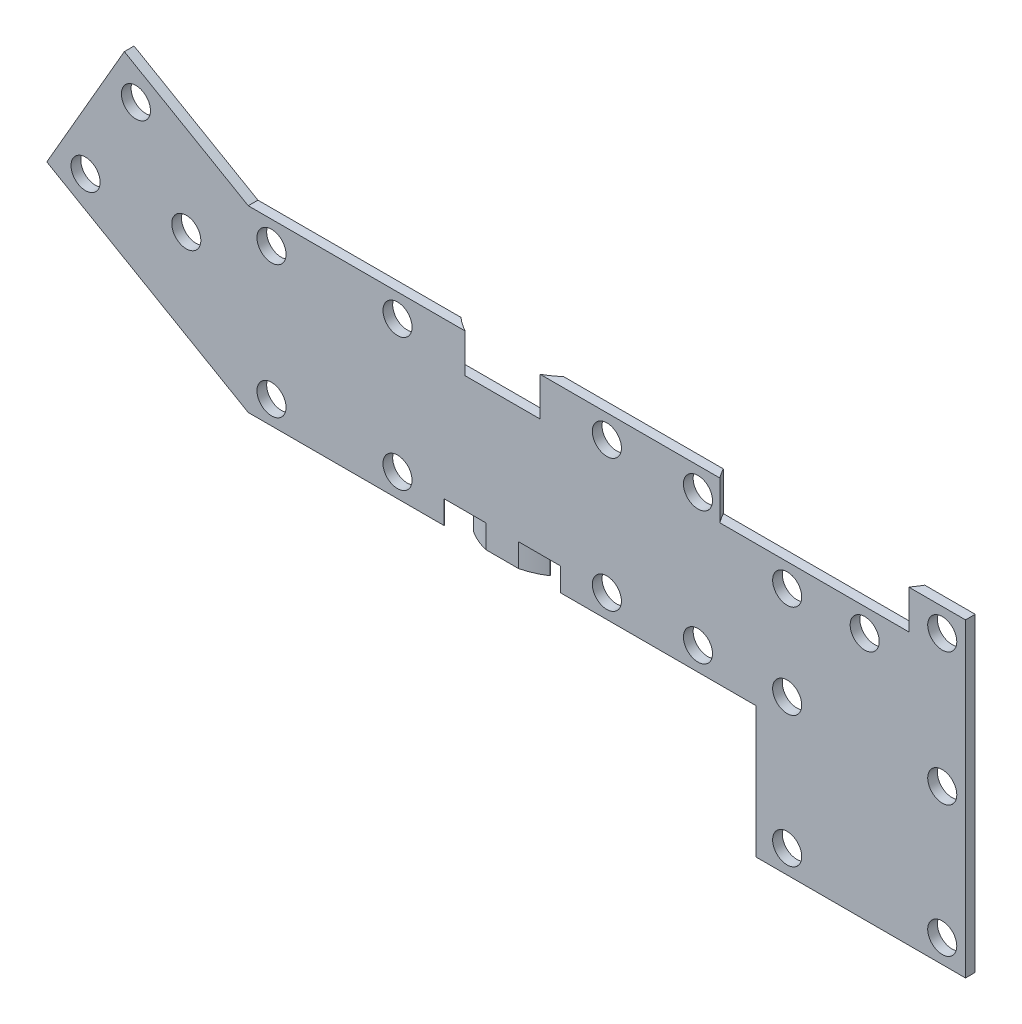
SolidWorks part; units mm, degrees
material "1023 Carbon Steel Sheet (SS)"
ref_plane "Front Plane" through (0, 0, 0) normal (0, 0, 1) x (1, 0, 0)
ref_plane "Top Plane" through (0, 0, 0) normal (0, 1, 0) x (1, 0, 0)
ref_plane "Right Plane" through (0, 0, 0) normal (1, 0, 0) x (0, 0, -1)
sketch "Sketch1" plane through (0, 0, 0) normal (0, 0, 1) x (1, 0, 0)
  line L0 (0, 0) -> (-40.5911, 23.4353)
  line L1 (-40.5911, 23.4353) -> (-65.9911, -20.5588)
  line L2 (-65.9911, -20.5588) -> (0, -58.6588)
  line L3 (0, -58.6588) -> (64.135, -58.6588)
  line L4 (64.135, -58.6588) -> (64.135, -51.0388)
  line L5 (64.135, -51.0388) -> (70.612, -51.0388)
  line L6 (70.612, -51.0388) -> (70.612, -58.6588)
  line L7 (70.612, -58.6588) -> (95.758, -58.6588)
  line L8 (95.758, -58.6588) -> (95.758, -51.0388)
  line L9 (95.758, -51.0388) -> (102.235, -51.0388)
  line L10 (102.235, -51.0388) -> (102.235, -58.6588)
  line L11 (102.235, -58.6588) -> (166.37, -58.6588)
  line L12 (166.37, -58.6588) -> (166.37, -101.6)
  line L13 (166.37, -101.6) -> (234.95, -101.6)
  line L14 (234.95, -101.6) -> (234.95, 0)
  line L23 (234.95, 0) -> (0, 0)
  circle A1 centre (-20.2956, -17.6117) radius 4.7625
  circle A2 centre (-53.2911, -17.6117) radius 4.7625
  circle A3 centre (-36.7934, 10.9633) radius 4.7625
  circle A4 centre (-36.7934, -8.0867) radius 19.05 construction
  circle A5 centre (7.62, -51.0388) radius 4.7625
  circle A6 centre (7.62, -7.62) radius 4.7625
  circle A7 centre (48.895, -7.62) radius 4.7625
  circle A8 centre (117.475, -7.62) radius 4.7625
  circle A9 centre (147.32, -7.62) radius 4.7625
  circle A10 centre (117.475, -51.0388) radius 4.7625
  circle A11 centre (48.895, -51.0388) radius 4.7625
  circle A12 centre (147.32, -51.0388) radius 4.7625
  circle A13 centre (176.53, -20.32) radius 4.7625
  circle A14 centre (201.93, -20.32) radius 4.7625
  circle A15 centre (227.33, -7.62) radius 4.7625
  circle A16 centre (227.33, -93.98) radius 4.7625
  circle A17 centre (176.53, -93.98) radius 4.7625
  circle A18 centre (227.33, -51.0388) radius 4.7625
  circle A19 centre (176.53, -51.0388) radius 4.7625
  point P3 (-36.7934, -8.0867)
  point P18 (232.0925, 0)
  point P19 (0, 0)
  point P28 (-53.2911, 1.4383)
  point P33 (83.185, -58.6588)
  dimension "D18" = 9.525
  dimension "D21" = 3
  dimension "D16" = 38.1
  dimension "D17" = 7.62
  dimension "D1" = 30
  dimension "D2" = 76.2
  dimension "D3" = 50.8
  dimension "D4" = 83.185
  dimension "D5" = 234.95
  dimension "D6" = 38.1
  dimension "D7" = 29.845
  dimension "D8" = 25.146
  dimension "D9" = 166.37
  dimension "D10" = 7.62
  dimension "D11" = 20.32
  dimension "D12" = 29.21
  dimension "D13" = 101.6
  dimension "D14" = 25.4
  dimension "D15" = 7.62
  dimension "D19" = 19.05
  dimension "D20" = 25.4
  dimension "D22" = 7.62
  dimension "D23" = 7.62
  dimension "D24" = 34.29
  dimension "D25" = 34.29
  dimension "D30" = 7.62
  dimension "D32" = 7.62
extrude "Boss-Extrude1" add sketch "Sketch1" along normal blind 3.175
sketch "Sketch2" plane through (0, -58.6588, 0) normal (0, -1, 0) x (1, 0, 0)
  line L0 (70.612, 0) -> (95.758, 0) construction
  line L3 (83.185, 0) -> (83.185, -19.05) construction
  circle A0 centre (83.185, -19.05) radius 22.86
  circle A1 centre (83.185, -19.05) radius 29.21
  point P2 (0, 0)
  point P3 (0, 0)
  point P4 (0, 0)
  dimension "D2" = 45.72
  dimension "D3" = 6.35
  dimension "D1" = 19.05
extrude "Cut-Extrude1" cut sketch "Sketch2" against normal blind 7.62
sketch "Sketch5" plane through (0, 0, 0) normal (0, 1, 0) x (1, 0, 0)
  line L0 (234.95, -1.5875) -> (185.42, -1.5875) construction
  line L1 (234.95, -3.175) -> (234.95, 0) construction
  line L2 (185.42, 0) -> (185.42, 19.05) construction
  line L5 (0, -1.5875) -> (83.312, -1.5875) construction
  line L6 (0, -3.175) -> (0, 0) construction
  line L7 (234.95, 0) -> (0, 0) construction
  circle A0 centre (185.42, 19.05) radius 38.1
  circle A1 centre (83.312, 19.05) radius 25.4
  point P5 (0, 0)
  point P7 (0, 0)
  point P17 (0, 0)
  point P18 (0, 0)
  point P19 (185.42, 21.2829)
  dimension "D3" = 76.2
  dimension "D5" = 50.8
  dimension "D1" = 49.53
  dimension "D2" = 19.05
  dimension "D4" = 83.312
extrude "Cut-Extrude5" cut sketch "Sketch5" against normal blind 12.7
